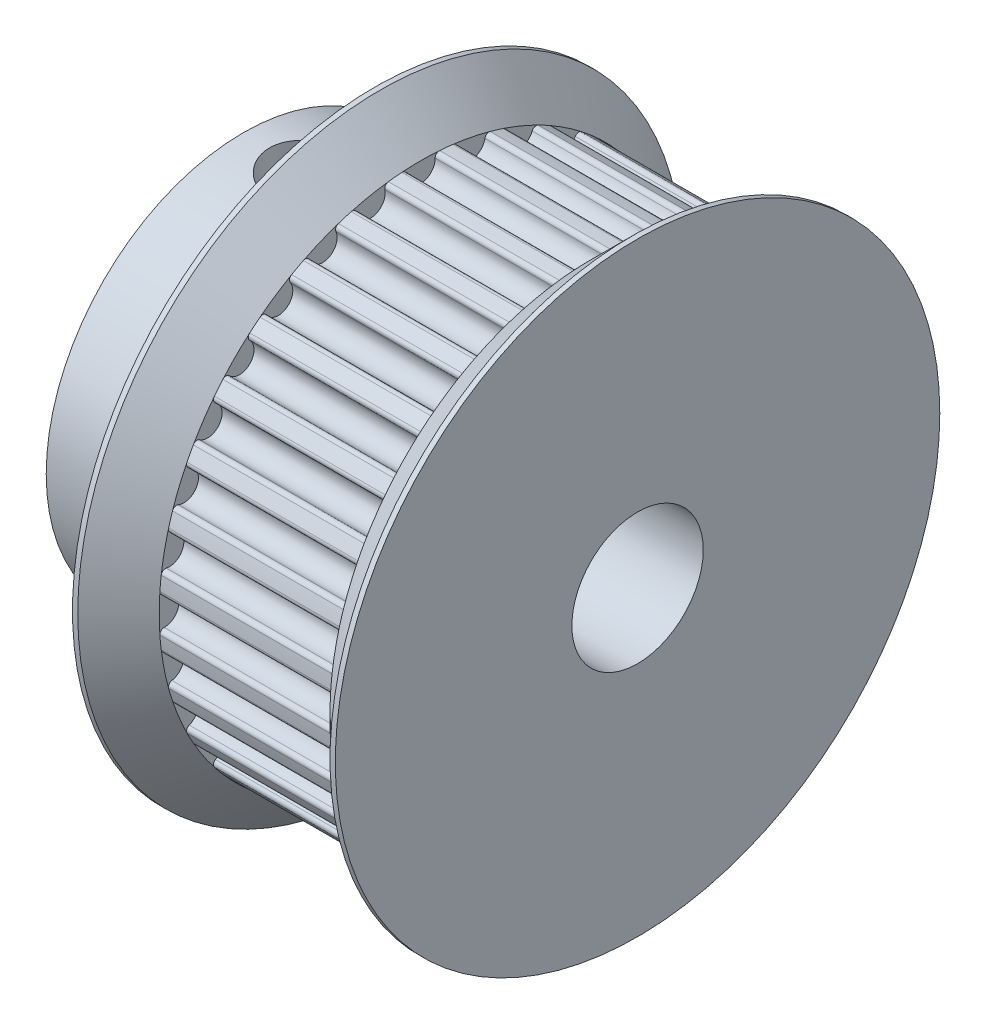
SolidWorks part; units mm, degrees
material "PLA Generic"
ref_plane "Front Plane" through (0, 0, 0) normal (0, 0, 1) x (1, 0, 0)
ref_plane "Top Plane" through (0, 0, 0) normal (0, 1, 0) x (1, 0, 0)
ref_plane "Right Plane" through (0, 0, 0) normal (1, 0, 0) x (0, 0, -1)
sketch "Sketch1" plane through (0, 0, 0) normal (0, 1, 0) x (1, 0, 0)
  line L0 (0, 0) -> (-15.0604, 0) construction
  line L1 (-1.75, 9.95) -> (-8.25, 9.95)
  line L2 (-10, 11.5) -> (-10, 2.5)
  line L3 (-10, 2.5) -> (0, 2.5)
  line L4 (0, 2.5) -> (0, 11.5)
  line L5 (-0.2, 11.5) -> (-1.75, 9.95)
  line L6 (-5, 9.95) -> (-5, 11.9782) construction
  line L7 (-9.8, 11.5) -> (-8.25, 9.95)
  line L8 (-10, 11.5) -> (-9.8, 11.5)
  line L9 (-0.2, 11.5) -> (0, 11.5)
  dimension "D1" = 6.5
  dimension "D2" = 19.9
  dimension "D3" = 23
  dimension "D4" = 5
  dimension "D5" = 135
  dimension "D6" = 10
revolve "Revolve1" add sketch "Sketch1" angle 360 about L0
ref_plane "Plane1" through (-1.75, 0, 0) normal (1, 0, 0) x (0, 0, -1)
ref_plane "Plane2" through (-8.25, 0, 0) normal (1, 0, 0) x (0, 0, -1)
sketch "Sketch2" plane through (-1.75, 0, 0) normal (1, 0, 0) x (0, 0, -1)
  circle A0 centre (0, 9.75) radius 0.55
  circle A1 centre (1.9021, 9.5627) radius 0.55
  circle A2 centre (3.7312, 9.0078) radius 0.55
  circle A3 centre (5.4168, 8.1068) radius 0.55
  circle A4 centre (6.8943, 6.8943) radius 0.55
  circle A5 centre (8.1068, 5.4168) radius 0.55
  circle A6 centre (9.0078, 3.7312) radius 0.55
  circle A7 centre (9.5627, 1.9021) radius 0.55
  circle A8 centre (9.75, 0) radius 0.55
  circle A9 centre (9.5627, -1.9021) radius 0.55
  circle A10 centre (9.0078, -3.7312) radius 0.55
  circle A11 centre (8.1068, -5.4168) radius 0.55
  circle A12 centre (6.8943, -6.8943) radius 0.55
  circle A13 centre (5.4168, -8.1068) radius 0.55
  circle A14 centre (3.7312, -9.0078) radius 0.55
  circle A15 centre (1.9021, -9.5627) radius 0.55
  circle A16 centre (0, -9.75) radius 0.55
  circle A17 centre (-1.9021, -9.5627) radius 0.55
  circle A18 centre (-3.7312, -9.0078) radius 0.55
  circle A19 centre (-5.4168, -8.1068) radius 0.55
  circle A20 centre (-6.8943, -6.8943) radius 0.55
  circle A21 centre (-8.1068, -5.4168) radius 0.55
  circle A22 centre (-9.0078, -3.7312) radius 0.55
  circle A23 centre (-9.5627, -1.9021) radius 0.55
  circle A24 centre (-9.75, 0) radius 0.55
  circle A25 centre (-9.5627, 1.9021) radius 0.55
  circle A26 centre (-9.0078, 3.7312) radius 0.55
  circle A27 centre (-8.1068, 5.4168) radius 0.55
  circle A28 centre (-6.8943, 6.8943) radius 0.55
  circle A29 centre (-5.4168, 8.1068) radius 0.55
  circle A30 centre (-3.7312, 9.0078) radius 0.55
  circle A31 centre (-1.9021, 9.5627) radius 0.55
  point P68 (0, 0)
  dimension "D1" = 9.75
  dimension "D2" = 1.1
  dimension "D3" = 32
extrude "Cut-Extrude1" cut sketch "Sketch2" against normal up to surface (6.5 mm away) up to plane "Plane2"
fillet "Fillet1" radius 0.16 64 edges at (-5, -0.5174, 9.9365) (-5, 0.5174, 9.9365) (-5, 1.4311, 9.8466) (-5, 2.446, 9.6447) (-5, 3.3245, 9.3782) (-5, 4.2806, 8.9822) (-5, 5.0902, 8.5494) (-5, 5.9506, 7.9745) (-5, 6.6603, 7.3921) (-5, 7.3921, 6.6603) (-5, 7.9745, 5.9506) (-5, 8.5494, 5.0902) (-5, 8.9822, 4.2806) (-5, 9.3782, 3.3245) (-5, 9.6447, 2.446) (-5, 9.8466, 1.4311) (-5, 9.9365, 0.5174) (-5, 9.9365, -0.5174) (-5, 9.8466, -1.4311) (-5, 9.6447, -2.446) (-5, 9.3782, -3.3245) (-5, 8.9822, -4.2806) (-5, 8.5494, -5.0902) (-5, 7.9745, -5.9506) (-5, 7.3921, -6.6603) (-5, 6.6603, -7.3921) (-5, 5.9506, -7.9745) (-5, 5.0902, -8.5494) (-5, 4.2806, -8.9822) (-5, 3.3245, -9.3782) (-5, 2.446, -9.6447) (-5, 1.4311, -9.8466) (-5, 0.5174, -9.9365) (-5, -0.5174, -9.9365) (-5, -1.4311, -9.8466) (-5, -2.446, -9.6447) (-5, -3.3245, -9.3782) (-5, -4.2806, -8.9822) (-5, -5.0902, -8.5494) (-5, -5.9506, -7.9745) (-5, -6.6603, -7.3921) (-5, -7.3921, -6.6603) (-5, -7.9745, -5.9506) (-5, -8.5494, -5.0902) (-5, -8.9822, -4.2806) (-5, -9.3782, -3.3245) (-5, -9.6447, -2.446) (-5, -9.8466, -1.4311) (-5, -9.9365, -0.5174) (-5, -9.9365, 0.5174) (-5, -9.8466, 1.4311) (-5, -9.6447, 2.446) (-5, -9.3782, 3.3245) (-5, -8.9822, 4.2806) (-5, -8.5494, 5.0902) (-5, -7.9745, 5.9506) (-5, -2.446, 9.6447) (-5, -1.4311, 9.8466) (-5, -4.2806, 8.9822) (-5, -3.3245, 9.3782) (-5, -5.9506, 7.9745) (-5, -5.0902, 8.5494) (-5, -7.3921, 6.6603) (-5, -6.6603, 7.3921)
sketch "Sketch3" plane through (-10, 0, 0) normal (-1, 0, 0) x (0, 0, 1)
  circle A0 centre (0, 0) radius 7.5
  circle A1 centre (0, 0) radius 2.5
  dimension "D1" = 15
  dimension "D2" = 5
extrude "Boss-Extrude1" add sketch "Sketch3" along normal blind 5
sketch "Sketch4" plane through (0, 0, 0) normal (0, 1, 0) x (1, 0, 0)
  line L0 (-15, 7.5) -> (-15, -7.5) construction
  circle A0 centre (-12.5, 0) radius 1.5
  dimension "D1" = 2.5
  dimension "D2" = 3
extrude "Cut-Extrude2" cut sketch "Sketch4" against normal through all and the other way through all
